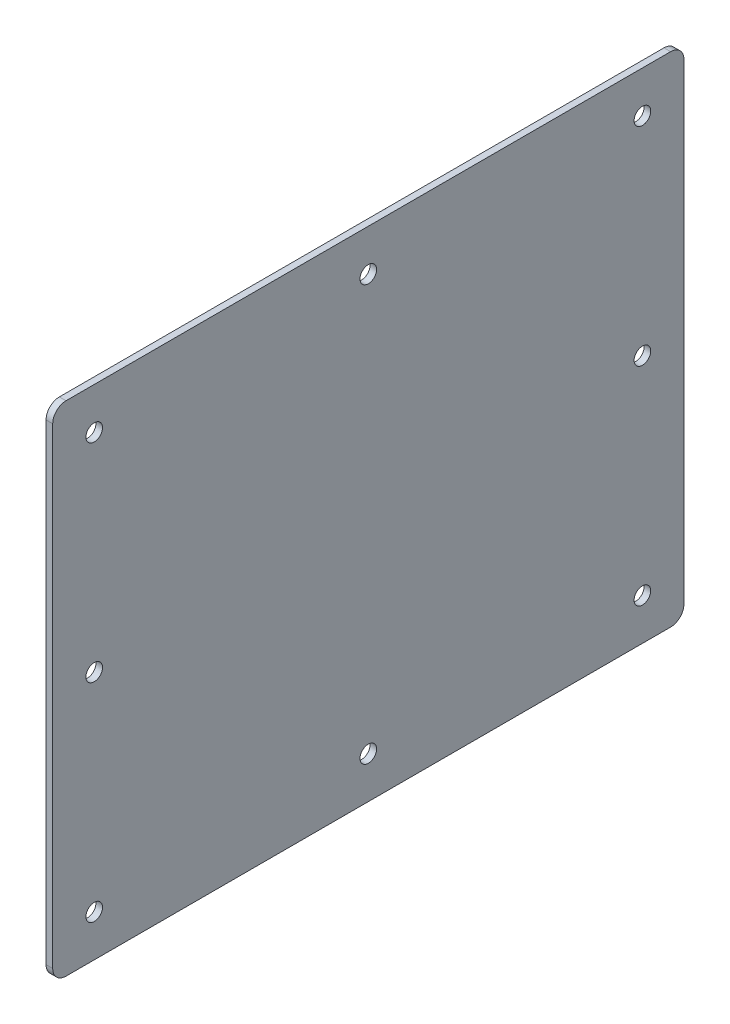
SolidWorks part; units mm, degrees
ref_plane "Front Plane" through (0, 0, 0) normal (1, 0, 0) x (0, 1, 0)
ref_plane "Top Plane" through (0, 0, 0) normal (0, 0, 1) x (0, 1, 0)
ref_plane "Right Plane" through (0, 0, 0) normal (0, 1, 0) x (-1, 0, 0)
sketch "Sketch1" plane through (0, 0, 0) normal (1, 0, 0) x (0, 1, 0)
  line L1 (-95.25, 120.65) -> (95.25, 120.65)
  line L2 (-95.25, 120.65) -> (-95.25, -120.65)
  line L3 (-95.25, -120.65) -> (95.25, -120.65)
  line L4 (95.25, 120.65) -> (95.25, -120.65)
  line L5 (-95.25, 120.65) -> (95.25, -120.65) construction
  line L6 (-95.25, -120.65) -> (95.25, 120.65) construction
  point P0 (0, 0)
  dimension "D1" = 190.5
  dimension "D2" = 241.3
extrude "Boss-Extrude1" add sketch "Sketch1" along normal blind 2.54
fillet "Fillet1" radius 5.08 4 edges at (1.27, 95.25, -120.65) (1.27, -95.25, -120.65) (1.27, -95.25, 120.65) (1.27, 95.25, 120.65)
sketch "Sketch2" plane through (2.54, 0, 0) normal (1, 0, 0) x (0, 0, -1)
  circle A1 centre (-574.675, 0) radius 3.175
  circle A2 centre (-574.675, 0) radius 3.175
  circle A3 centre (-725.4875, 79.375) radius 3.175
  circle A4 centre (-725.4875, 79.375) radius 3.175
  circle A5 centre (-831.85, 79.375) radius 3.175
  circle A6 centre (-831.85, 79.375) radius 3.175
  circle A7 centre (-938.2125, 79.375) radius 3.175
  circle A8 centre (-938.2125, 79.375) radius 3.175
  circle A9 centre (-1044.575, 79.375) radius 3.175
  circle A10 centre (-1044.575, 79.375) radius 3.175
  circle A11 centre (-1044.575, -79.375) radius 3.175
  circle A12 centre (-1044.575, -79.375) radius 3.175
  circle A13 centre (-1044.575, 0) radius 3.175
  circle A14 centre (-1044.575, 0) radius 3.175
  circle A15 centre (-574.675, 79.375) radius 3.175
  circle A16 centre (-574.675, 79.375) radius 3.175
  circle A17 centre (-468.3125, 79.375) radius 3.175
  circle A18 centre (-468.3125, 79.375) radius 3.175
  circle A19 centre (-574.675, -79.375) radius 3.175
  circle A20 centre (-574.675, -79.375) radius 3.175
  circle A21 centre (-725.4875, -79.375) radius 3.175
  circle A22 centre (-725.4875, -79.375) radius 3.175
  circle A23 centre (-619.125, -79.375) radius 3.175
  circle A24 centre (-619.125, -79.375) radius 3.175
  circle A25 centre (-619.125, 0) radius 3.175
  circle A26 centre (-619.125, 0) radius 3.175
  circle A27 centre (-619.125, 79.375) radius 3.175
  circle A28 centre (-619.125, 79.375) radius 3.175
  circle A29 centre (-255.5875, 79.375) radius 3.175
  circle A30 centre (-255.5875, 79.375) radius 3.175
  circle A31 centre (-361.95, 79.375) radius 3.175
  circle A32 centre (-361.95, 79.375) radius 3.175
  circle A33 centre (-938.2125, -79.375) radius 3.175
  circle A34 centre (-938.2125, -79.375) radius 3.175
  circle A35 centre (-831.85, -79.375) radius 3.175
  circle A36 centre (-831.85, -79.375) radius 3.175
  circle A37 centre (-149.225, -79.375) radius 3.175
  circle A38 centre (-149.225, -79.375) radius 3.175
  circle A39 centre (-255.5875, -79.375) radius 3.175
  circle A40 centre (-255.5875, -79.375) radius 3.175
  circle A41 centre (-149.225, 79.375) radius 3.175
  circle A42 centre (-149.225, 79.375) radius 3.175
  circle A43 centre (-361.95, -79.375) radius 3.175
  circle A44 centre (-361.95, -79.375) radius 3.175
  circle A45 centre (-149.225, 0) radius 3.175
  circle A46 centre (-149.225, 0) radius 3.175
  circle A47 centre (-468.3125, -79.375) radius 3.175
  circle A48 centre (-468.3125, -79.375) radius 3.175
  circle A49 centre (0, 79.375) radius 3.175
  circle A50 centre (0, 79.375) radius 3.175
  circle A51 centre (0, -79.375) radius 3.175
  circle A52 centre (0, -79.375) radius 3.175
  circle A53 centre (-104.775, -79.375) radius 3.175
  circle A54 centre (-104.775, -79.375) radius 3.175
  circle A55 centre (-104.775, 79.375) radius 3.175
  circle A56 centre (-104.775, 79.375) radius 3.175
  circle A57 centre (104.775, 0) radius 3.175
  circle A58 centre (104.775, 0) radius 3.175
  circle A59 centre (-104.775, 0) radius 3.175
  circle A60 centre (-104.775, 0) radius 3.175
  circle A61 centre (104.775, -79.375) radius 3.175
  circle A62 centre (104.775, -79.375) radius 3.175
  circle A63 centre (104.775, 79.375) radius 3.175
  circle A64 centre (104.775, 79.375) radius 3.175
  dimension "D1" = 0
  dimension "D2" = 0
  dimension "D3" = 0
  dimension "D4" = 0
  dimension "D5" = 0
  dimension "D6" = 0
  dimension "D7" = 0
  dimension "D8" = 0
  dimension "D9" = 0
  dimension "D10" = 0
  dimension "D11" = 0
  dimension "D12" = 0
  dimension "D13" = 0
  dimension "D14" = 0
  dimension "D15" = 0
  dimension "D16" = 0
  dimension "D17" = 0
  dimension "D18" = 0
  dimension "D19" = 0
  dimension "D20" = 0
  dimension "D21" = 0
  dimension "D22" = 0
  dimension "D23" = 0
  dimension "D24" = 0
  dimension "D25" = 0
  dimension "D26" = 0
  dimension "D27" = 0
  dimension "D28" = 0
  dimension "D29" = 0
  dimension "D30" = 0
  dimension "D31" = 0
  dimension "D32" = 0
extrude "Cut-Extrude1" cut sketch "Sketch2" against normal through all both and the other way through all
